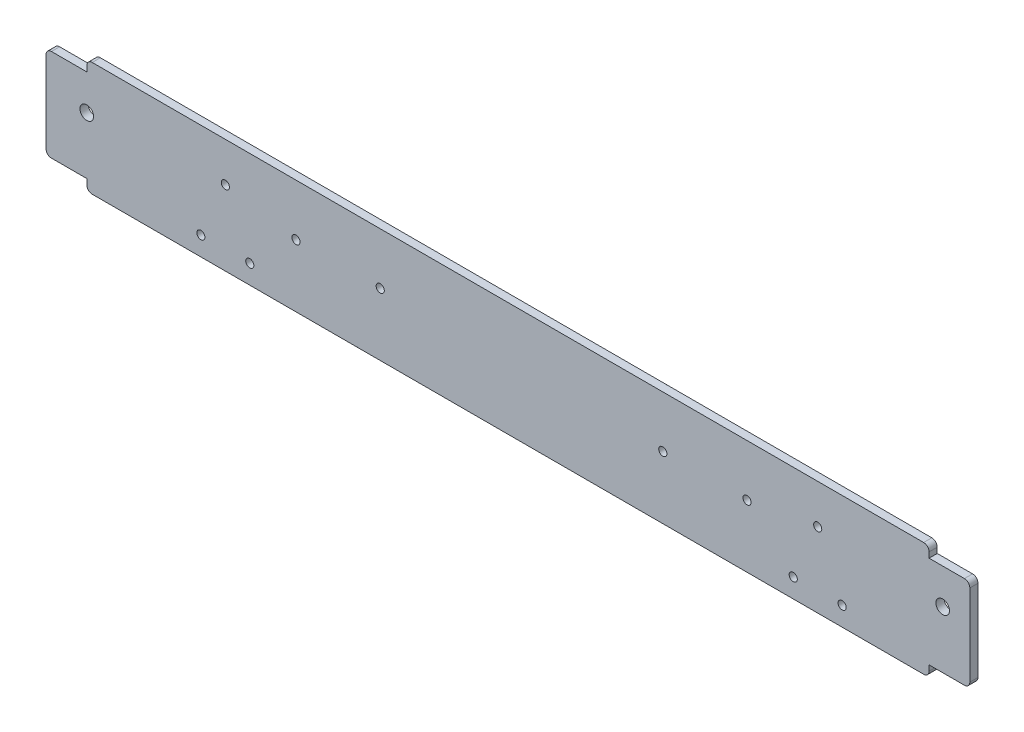
SolidWorks part; units mm, degrees
material "MDF"
ref_plane "Alzado" through (0, 0, 0) normal (0, 0, 1) x (1, 0, 0)
ref_plane "Planta" through (0, 0, 0) normal (0, 1, 0) x (1, 0, 0)
ref_plane "Vista lateral" through (0, 0, 0) normal (1, 0, 0) x (0, 0, -1)
sketch "Croquis1" plane through (0, 0, 0) normal (0, 0, 1) x (1, 0, 0)
  line L1 (-170, 21) -> (170, 21)
  line L2 (-170, 21) -> (-170, -21)
  line L3 (-170, -21) -> (170, -21)
  line L4 (170, 21) -> (170, -21)
  line L5 (-170, 21) -> (170, -21) construction
  line L6 (-170, -21) -> (170, 21) construction
  line L7 (105, -14) -> (123, -14) construction
  circle A1 centre (-47, 2) radius 1.5
  circle A2 centre (-78, 2) radius 1.5
  circle A3 centre (-104, 6.5) radius 1.5
  circle A4 centre (-113, -14) radius 1.5
  circle A5 centre (-95, -14) radius 1.5
  circle A7 centre (-155, 4) radius 2.5
  circle A9 centre (160, 4) radius 2.5
  circle A12 centre (114, 6.5) radius 1.5
  circle A13 centre (105, -14) radius 1.5
  circle A14 centre (123, -14) radius 1.5
  circle A15 centre (88, 2) radius 1.5
  circle A16 centre (57, 2) radius 1.5
  point P0 (0, 0)
  point P10 (114, -14)
  dimension "D9" = 3
  dimension "D11" = 23
  dimension "D23" = 5
  dimension "D19" = 5
  dimension "D1" = 42
  dimension "D6" = 23
  dimension "D7" = 82
  dimension "D8" = 340
  dimension "D10" = 23
  dimension "D12" = 31
  dimension "D13" = 92
  dimension "D14" = 27.5
  dimension "D15" = 66
  dimension "D16" = 7
  dimension "D17" = 18
  dimension "D18" = 57
  dimension "D20" = 25
  dimension "D24" = 10
  dimension "D25" = 25
  dimension "D27" = 27.5
  dimension "D28" = 56
  dimension "D29" = 18
  dimension "D30" = 7
  dimension "D32" = 31
  dimension "D21" = 15
extrude "Saliente-Extruir1" add sketch "Croquis1" along normal blind 3
sketch "Croquis2" plane through (0, 0, 3) normal (0, 0, 1) x (1, 0, 0)
  line L0 (-170, -17) -> (-155, -17)
  line L1 (-170, 21) -> (-170, -21) construction
  line L2 (-155, -17) -> (-155, -21)
  line L3 (-170, -21) -> (170, -21) construction
  line L4 (-170, -17) -> (-170, -21)
  line L5 (-170, -21) -> (-155, -21)
  dimension "D1" = 4
  dimension "D2" = 15
extrude "Cortar-Extruir2" cut sketch "Croquis2" against normal through all
mirror "Simetría4" about plane through (0, 0, 0) normal (1, 0, 0) of "Cortar-Extruir2" second plane through (0, 0, 0) second plane normal (0, 1, 0)
fillet "Redondeo1" radius 2 8 edges at (155, -21, 1.5) (170, 17, 1.5) (155, 21, 1.5) (-170, -17, 1.5) (-155, -21, 1.5) (-170, 17, 1.5) (-155, 21, 1.5) (170, -17, 1.5)
